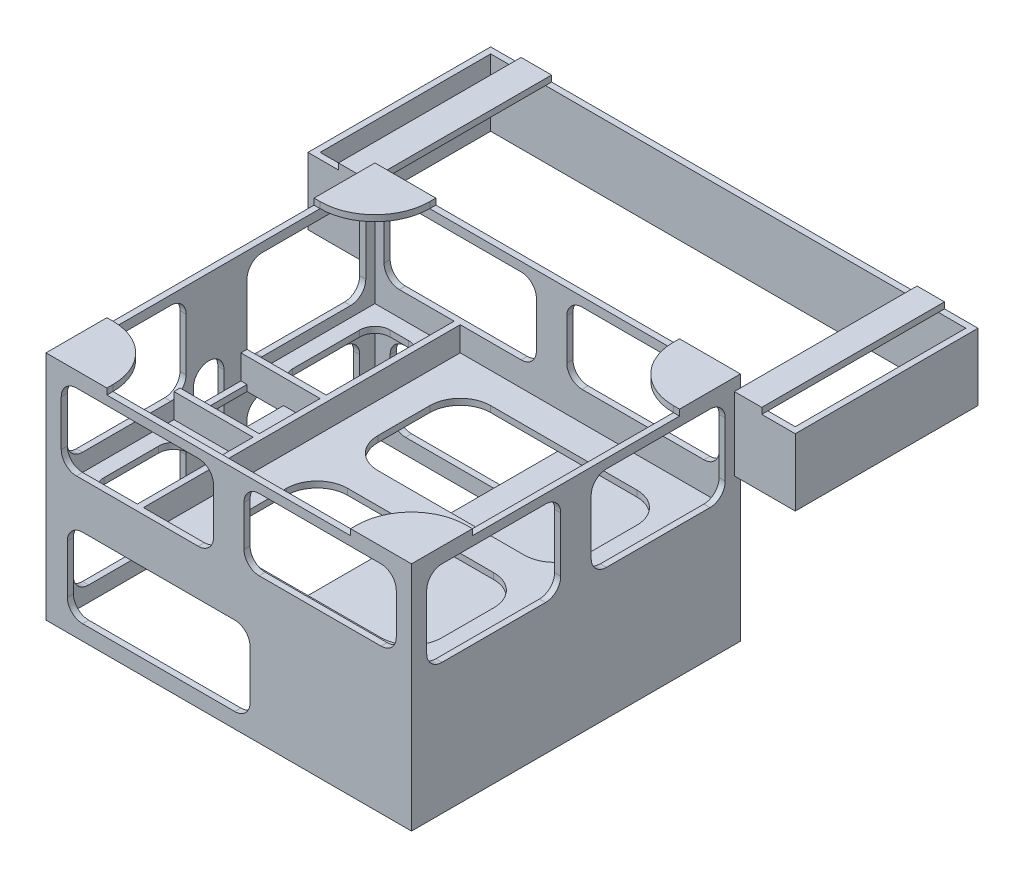
SolidWorks part; units mm, degrees
ref_plane "Front Plane" through (0, 0, 0) normal (0, 0, 1) x (1, 0, 0)
ref_plane "Top Plane" through (0, 0, 0) normal (0, 1, 0) x (1, 0, 0)
ref_plane "Right Plane" through (0, 0, 0) normal (1, 0, 0) x (0, 0, -1)
sketch "Sketch1" plane through (0, 0, 0) normal (0, 1, 0) x (1, 0, 0)
  line L1 (-113.8745, -60.9464) -> (-53.8745, -60.9464)
  line L2 (-113.8745, -60.9464) -> (-113.8745, -6.9464)
  line L3 (-113.8745, -6.9464) -> (-53.8745, -6.9464)
  line L4 (-53.8745, -60.9464) -> (-53.8745, -6.9464)
  dimension "D1" = 60
  dimension "D2" = 54
extrude "Boss-Extrude1" add sketch "Sketch1" along normal blind 38
sketch "Sketch2" plane through (0, 38, 0) normal (0, 1, 0) x (1, 0, 0)
  line L0 (-53.8745, -60.9464) -> (-53.8745, -6.9464) construction
  line L1 (-54.8745, -7.9464) -> (-98.8745, -7.9464)
  line L2 (-54.8745, -7.9464) -> (-54.8745, -59.9464)
  line L3 (-54.8745, -59.9464) -> (-98.8745, -59.9464)
  line L4 (-98.8745, -7.9464) -> (-98.8745, -59.9464)
  line L5 (-53.8745, -6.9464) -> (-113.8745, -6.9464) construction
  line L6 (-113.8745, -60.9464) -> (-53.8745, -60.9464) construction
  dimension "D1" = 1
  dimension "D2" = 1
  dimension "D3" = 1
  dimension "D4" = 44
extrude "Cut-Extrude1" cut sketch "Sketch2" against normal blind 19
sketch "Sketch3" plane through (0, 0, 0) normal (0, -1, 0) x (-1, 0, 0)
  line L0 (113.8745, -60.9464) -> (53.8745, -60.9464) construction
  line L1 (112.8745, -59.9464) -> (77.8745, -59.9464)
  line L2 (112.8745, -59.9464) -> (112.8745, -7.9464)
  line L3 (112.8745, -7.9464) -> (77.8745, -7.9464)
  line L4 (77.8745, -59.9464) -> (77.8745, -7.9464)
  line L5 (113.8745, -6.9464) -> (113.8745, -60.9464) construction
  line L6 (53.8745, -6.9464) -> (113.8745, -6.9464) construction
  dimension "D1" = 1
  dimension "D2" = 35
  dimension "D3" = 1
  dimension "D4" = 1
extrude "Cut-Extrude2" cut sketch "Sketch3" against normal blind 18
sketch "Sketch4" plane through (0, 18, 0) normal (0, -1, 0) x (-1, 0, 0)
  line L0 (77.8745, -59.9464) -> (112.8745, -59.9464) construction
  line L1 (111.8745, -39.9464) -> (105.8745, -39.9464)
  line L2 (111.8745, -39.9464) -> (111.8745, -29.9464)
  line L3 (111.8745, -29.9464) -> (105.8745, -29.9464)
  line L4 (105.8745, -39.9464) -> (105.8745, -29.9464)
  line L5 (112.8745, -7.9464) -> (77.8745, -7.9464) construction
  line L6 (112.8745, -59.9464) -> (112.8745, -7.9464) construction
  dimension "D1" = 20
  dimension "D2" = 22
  dimension "D3" = 1
  dimension "D4" = 6
extrude "Cut-Extrude3" cut sketch "Sketch4" against normal blind 38
sketch "Sketch5" plane through (0, 38, 0) normal (0, 1, 0) x (1, 0, 0)
  line L0 (-53.8745, -6.9464) -> (-113.8745, -6.9464) construction
  line L1 (-98.8745, -59.9464) -> (-112.8745, -59.9464)
  line L2 (-98.8745, -59.9464) -> (-98.8745, -7.9464)
  line L3 (-98.8745, -7.9464) -> (-112.8745, -7.9464)
  line L4 (-112.8745, -59.9464) -> (-112.8745, -7.9464)
  line L5 (-113.8745, -6.9464) -> (-113.8745, -60.9464) construction
  dimension "D1" = 1
  dimension "D2" = 1
extrude "Cut-Extrude5" cut sketch "Sketch5" against normal blind 15
sketch "Sketch6" plane through (0, 23, 0) normal (0, 1, 0) x (1, 0, 0)
  line L0 (-112.8745, -59.9464) -> (-98.8745, -59.9464) construction
  line L1 (-112.8745, -7.9464) -> (-99.8745, -7.9464)
  line L2 (-112.8745, -7.9464) -> (-112.8745, -59.9464)
  line L3 (-112.8745, -59.9464) -> (-99.8745, -59.9464)
  line L4 (-99.8745, -7.9464) -> (-99.8745, -59.9464)
  line L5 (-98.8745, -59.9464) -> (-98.8745, -7.9464) construction
  dimension "D1" = 1
extrude "Cut-Extrude6" cut sketch "Sketch6" against normal blind 4
sketch "Sketch8" plane through (0, 0, 0) normal (0, -1, 0) x (-1, 0, 0)
  line L0 (53.8745, -60.9464) -> (53.8745, -6.9464) construction
  line L1 (73.3745, -11.4464) -> (58.3745, -11.4464)
  line L2 (73.3745, -11.4464) -> (73.3745, -24.4464)
  line L3 (73.3745, -24.4464) -> (58.3745, -24.4464)
  line L4 (58.3745, -11.4464) -> (58.3745, -24.4464)
  line L6 (53.8745, -6.9464) -> (113.8745, -6.9464) construction
  dimension "D1" = 15
  dimension "D2" = 13
  dimension "D3" = 4.5
  dimension "D4" = 4.5
extrude "Cut-Extrude7" cut sketch "Sketch8" against normal blind 6
sketch "Sketch10" plane through (-73.3745, 0, 0) normal (1, 0, 0) x (0, 0, -1)
  line L0 (-11.4464, 6) -> (-11.4464, 0) construction
  line L1 (-24.4464, 6) -> (-11.4464, 6)
  line L2 (-24.4464, 6) -> (-24.4464, 1)
  line L3 (-24.4464, 1) -> (-11.4464, 1)
  line L4 (-11.4464, 6) -> (-11.4464, 1)
  line L5 (-24.4464, 0) -> (-11.4464, 0) construction
  dimension "D1" = 1
extrude "Cut-Extrude8" cut sketch "Sketch10" against normal blind 6
sketch "Sketch11" plane through (0, 0, 0) normal (0, -1, 0) x (1, 0, 0)
  line L0 (-113.8745, 60.9464) -> (-53.8745, 60.9464) construction
  line L1 (-67.8745, 50.9464) -> (-63.8745, 50.9464)
  line L2 (-67.8745, 50.9464) -> (-67.8745, 45.9464)
  line L3 (-67.8745, 45.9464) -> (-63.8745, 45.9464)
  line L4 (-63.8745, 50.9464) -> (-63.8745, 45.9464)
  line L5 (-53.8745, 60.9464) -> (-53.8745, 6.9464) construction
  dimension "D1" = 4
  dimension "D2" = 5
  dimension "D3" = 10
  dimension "D4" = 10
extrude "Cut-Extrude9" cut sketch "Sketch11" against normal blind 3
sketch "Sketch12" plane through (-67.8745, 0, 0) normal (1, 0, 0) x (0, 0, -1)
  line L0 (-50.9464, 3) -> (-50.9464, 0) construction
  line L1 (-45.9464, 3) -> (-50.9464, 3)
  line L2 (-45.9464, 3) -> (-45.9464, 1)
  line L3 (-45.9464, 1) -> (-50.9464, 1)
  line L4 (-50.9464, 3) -> (-50.9464, 1)
  line L5 (-50.9464, 0) -> (-45.9464, 0) construction
  dimension "D1" = 1
extrude "Cut-Extrude10" cut sketch "Sketch12" against normal blind 13
sketch "Sketch13" plane through (-113.8745, 0, 0) normal (-1, 0, 0) x (0, 0, 1)
  line L0 (35.233, 15) -> (35.233, 22) construction
  line L1 (32.733, 15) -> (32.733, 22)
  line L2 (37.733, 15) -> (37.733, 22)
  line L3 (59.9464, 18) -> (7.9464, 18) construction
  line L4 (39.9464, 19) -> (29.9464, 19) construction
  arc A0 (32.733, 15) -> (37.733, 15) centre (35.233, 15) ccw
  arc A1 (37.733, 22) -> (32.733, 22) centre (35.233, 22) ccw
  point P2 (35.233, 18.5)
  dimension "D1" = 3
  dimension "D2" = 3
  dimension "D3" = 2.5
extrude "Cut-Extrude11" cut sketch "Sketch13" against normal blind 1
sketch "Sketch14" plane through (0, 19, 0) normal (0, 1, 0) x (1, 0, 0)
  line L0 (-99.8745, -59.9464) -> (-99.8745, -7.9464) construction
  line L1 (-112.8745, -40.9464) -> (-99.8745, -40.9464)
  line L2 (-112.8745, -40.9464) -> (-112.8745, -39.9464)
  line L3 (-112.8745, -39.9464) -> (-99.8745, -39.9464)
  line L4 (-99.8745, -40.9464) -> (-99.8745, -39.9464)
  line L5 (-112.8745, -37.733) -> (-112.8745, -59.9464) construction
  line L6 (-105.8745, -39.9464) -> (-111.8745, -39.9464) construction
  dimension "D1" = 0
  dimension "D2" = 1
  dimension "D3" = 0
extrude "Boss-Extrude2" add sketch "Sketch14" along normal blind 4
sketch "Sketch15" plane through (0, 19, 0) normal (0, 1, 0) x (1, 0, 0)
  line L0 (-112.8745, -7.9464) -> (-112.8745, -32.733) construction
  line L1 (-112.8745, -29.9464) -> (-99.8745, -29.9464)
  line L2 (-112.8745, -29.9464) -> (-112.8745, -28.9464)
  line L3 (-112.8745, -28.9464) -> (-99.8745, -28.9464)
  line L4 (-99.8745, -29.9464) -> (-99.8745, -28.9464)
  line L5 (-99.8745, -39.9464) -> (-99.8745, -7.9464) construction
  line L6 (-111.8745, -29.9464) -> (-105.8745, -29.9464) construction
  dimension "D1" = 0
  dimension "D2" = 1
extrude "Boss-Extrude3" add sketch "Sketch15" along normal blind 4
sketch "Sketch16" plane through (0, 19, 0) normal (0, 1, 0) x (1, 0, 0)
  line L0 (-98.8745, -59.9464) -> (-54.8745, -59.9464) construction
  line L1 (-64.8745, -54.9464) -> (-88.8745, -54.9464)
  line L2 (-59.8745, -49.9464) -> (-59.8745, -41.4464)
  line L3 (-64.8745, -36.4464) -> (-88.8745, -36.4464)
  line L4 (-93.8745, -49.9464) -> (-93.8745, -41.4464)
  line L5 (-88.8745, -31.4464) -> (-64.8745, -31.4464)
  line L6 (-93.8745, -26.4464) -> (-93.8745, -17.9464)
  line L7 (-88.8745, -12.9464) -> (-64.8745, -12.9464)
  line L8 (-59.8745, -26.4464) -> (-59.8745, -17.9464)
  line L9 (-54.8745, -59.9464) -> (-54.8745, -7.9464) construction
  line L10 (-98.8745, -7.9464) -> (-98.8745, -59.9464) construction
  line L11 (-54.8745, -7.9464) -> (-98.8745, -7.9464) construction
  arc A0 (-64.8745, -31.4464) -> (-59.8745, -26.4464) centre (-64.8745, -26.4464) ccw
  arc A1 (-64.8745, -12.9464) -> (-59.8745, -17.9464) centre (-64.8745, -17.9464) cw
  arc A2 (-93.8745, -17.9464) -> (-88.8745, -12.9464) centre (-88.8745, -17.9464) cw
  arc A3 (-88.8745, -31.4464) -> (-93.8745, -26.4464) centre (-88.8745, -26.4464) cw
  arc A4 (-88.8745, -54.9464) -> (-93.8745, -49.9464) centre (-88.8745, -49.9464) cw
  arc A5 (-88.8745, -36.4464) -> (-93.8745, -41.4464) centre (-88.8745, -41.4464) ccw
  arc A6 (-59.8745, -41.4464) -> (-64.8745, -36.4464) centre (-64.8745, -41.4464) ccw
  arc A7 (-64.8745, -54.9464) -> (-59.8745, -49.9464) centre (-64.8745, -49.9464) ccw
  point P22 (-93.8745, -12.9464)
  point P25 (-93.8745, -31.4464)
  dimension "D9" = 5
  dimension "D1" = 5
  dimension "D2" = 5
  dimension "D3" = 5
  dimension "D4" = 5
  dimension "D5" = 5
  dimension "D6" = 5
  dimension "D7" = 5
  dimension "D8" = 18.5
extrude "Cut-Extrude12" cut sketch "Sketch16" against normal blind 1
sketch "Sketch17" plane through (0, 19, 0) normal (0, 1, 0) x (1, 0, 0)
  line L0 (-112.8745, -40.9464) -> (-112.8745, -59.9464) construction
  line L1 (-104.8745, -57.4464) -> (-107.8745, -57.4464)
  line L2 (-102.3745, -54.9464) -> (-102.3745, -45.9464)
  line L3 (-104.8745, -43.4464) -> (-107.8745, -43.4464)
  line L4 (-110.3745, -54.9464) -> (-110.3745, -45.9464)
  line L5 (-104.8745, -26.4464) -> (-107.8745, -26.4464)
  line L6 (-102.3745, -23.9464) -> (-102.3745, -12.9464)
  line L7 (-104.8745, -10.4464) -> (-107.8745, -10.4464)
  line L8 (-110.3745, -23.9464) -> (-110.3745, -12.9464)
  line L9 (-99.8745, -59.9464) -> (-99.8745, -40.9464) construction
  line L10 (-112.8745, -40.9464) -> (-99.8745, -40.9464) construction
  line L11 (-112.8745, -59.9464) -> (-99.8745, -59.9464) construction
  line L12 (-99.8745, -28.9464) -> (-112.8745, -28.9464) construction
  line L13 (-112.8745, -7.9464) -> (-112.8745, -28.9464) construction
  line L14 (-99.8745, -28.9464) -> (-99.8745, -7.9464) construction
  line L15 (-99.8745, -7.9464) -> (-112.8745, -7.9464) construction
  arc A0 (-102.3745, -12.9464) -> (-104.8745, -10.4464) centre (-104.8745, -12.9464) ccw
  arc A1 (-107.8745, -10.4464) -> (-110.3745, -12.9464) centre (-107.8745, -12.9464) ccw
  arc A2 (-107.8745, -26.4464) -> (-110.3745, -23.9464) centre (-107.8745, -23.9464) cw
  arc A3 (-104.8745, -26.4464) -> (-102.3745, -23.9464) centre (-104.8745, -23.9464) ccw
  arc A4 (-102.3745, -45.9464) -> (-104.8745, -43.4464) centre (-104.8745, -45.9464) ccw
  arc A5 (-107.8745, -43.4464) -> (-110.3745, -45.9464) centre (-107.8745, -45.9464) ccw
  arc A6 (-107.8745, -57.4464) -> (-110.3745, -54.9464) centre (-107.8745, -54.9464) cw
  arc A7 (-104.8745, -57.4464) -> (-102.3745, -54.9464) centre (-104.8745, -54.9464) ccw
  dimension "D9" = 2.5
  dimension "D1" = 2.5
  dimension "D2" = 2.5
  dimension "D3" = 2.5
  dimension "D4" = 2.5
  dimension "D5" = 2.5
  dimension "D6" = 2.5
  dimension "D7" = 2.5
  dimension "D8" = 2.5
extrude "Cut-Extrude13" cut sketch "Sketch17" against normal blind 1
sketch "Sketch18" plane through (-53.8745, 0, 0) normal (1, 0, 0) x (0, 0, -1)
  line L0 (-60.9464, 38) -> (-6.9464, 38) construction
  line L1 (-55.9464, 35.5) -> (-38.9464, 35.5)
  line L2 (-58.4464, 33) -> (-58.4464, 24)
  line L3 (-55.9464, 21.5) -> (-38.9464, 21.5)
  line L4 (-36.4464, 33) -> (-36.4464, 24)
  line L5 (-28.9464, 35.5) -> (-11.9464, 35.5)
  line L6 (-31.4464, 33) -> (-31.4464, 24)
  line L7 (-28.9464, 21.5) -> (-11.9464, 21.5)
  line L8 (-9.4464, 33) -> (-9.4464, 24)
  line L9 (-60.9464, 38) -> (-60.9464, 0) construction
  line L10 (-6.9464, 38) -> (-6.9464, 0) construction
  line L11 (-59.9464, 19) -> (-7.9464, 19) construction
  arc A0 (-31.4464, 24) -> (-28.9464, 21.5) centre (-28.9464, 24) ccw
  arc A1 (-11.9464, 21.5) -> (-9.4464, 24) centre (-11.9464, 24) ccw
  arc A2 (-11.9464, 35.5) -> (-9.4464, 33) centre (-11.9464, 33) cw
  arc A3 (-28.9464, 35.5) -> (-31.4464, 33) centre (-28.9464, 33) ccw
  arc A4 (-58.4464, 24) -> (-55.9464, 21.5) centre (-55.9464, 24) ccw
  arc A5 (-38.9464, 21.5) -> (-36.4464, 24) centre (-38.9464, 24) ccw
  arc A6 (-38.9464, 35.5) -> (-36.4464, 33) centre (-38.9464, 33) cw
  arc A7 (-55.9464, 35.5) -> (-58.4464, 33) centre (-55.9464, 33) ccw
  point P26 (-58.4464, 21.5)
  point P29 (-36.4464, 21.5)
  dimension "D9" = 2.5
  dimension "D1" = 2.5
  dimension "D2" = 2.5
  dimension "D3" = 2.5
  dimension "D4" = 2.5
  dimension "D5" = 5
  dimension "D6" = 22
  dimension "D7" = 2.5
  dimension "D8" = 2.5
extrude "Cut-Extrude14" cut sketch "Sketch18" against normal blind 1
sketch "Sketch19" plane through (0, 0, 6.9464) normal (0, 0, -1) x (-1, 0, 0)
  line L0 (53.8745, 38) -> (113.8745, 38) construction
  line L1 (58.8745, 35.5) -> (78.8745, 35.5)
  line L2 (56.3745, 33) -> (56.3745, 26.3041)
  line L3 (58.8745, 23.8041) -> (78.8745, 23.8041)
  line L4 (81.3745, 33) -> (81.3745, 26.3041)
  line L5 (88.8745, 35.5) -> (108.8745, 35.5)
  line L6 (86.3745, 33) -> (86.3745, 25.5)
  line L7 (88.8745, 23) -> (108.8745, 23)
  line L8 (111.3745, 33) -> (111.3745, 25.5)
  line L9 (113.8745, 38) -> (113.8745, 0) construction
  line L10 (53.8745, 38) -> (53.8745, 0) construction
  arc A0 (108.8745, 23) -> (111.3745, 25.5) centre (108.8745, 25.5) ccw
  arc A1 (108.8745, 35.5) -> (111.3745, 33) centre (108.8745, 33) cw
  arc A2 (88.8745, 35.5) -> (86.3745, 33) centre (88.8745, 33) ccw
  arc A3 (86.3745, 25.5) -> (88.8745, 23) centre (88.8745, 25.5) ccw
  arc A4 (78.8745, 23.8041) -> (81.3745, 26.3041) centre (78.8745, 26.3041) ccw
  arc A5 (78.8745, 35.5) -> (81.3745, 33) centre (78.8745, 33) cw
  arc A6 (56.3745, 26.3041) -> (58.8745, 23.8041) centre (58.8745, 26.3041) ccw
  arc A7 (58.8745, 35.5) -> (56.3745, 33) centre (58.8745, 33) ccw
  point P17 (111.3745, 23)
  point P24 (86.3745, 23)
  dimension "D8" = 2.5
  dimension "D1" = 2.5
  dimension "D2" = 2.5
  dimension "D3" = 2.5
  dimension "D4" = 2.5
  dimension "D5" = 5
  dimension "D6" = 25
  dimension "D7" = 0
extrude "Cut-Extrude15" cut sketch "Sketch19" against normal blind 60
sketch "Sketch20" plane through (-113.8745, 0, 0) normal (-1, 0, 0) x (0, 0, 1)
  line L0 (59.9464, 38) -> (7.9464, 38) construction
  line L1 (11.9464, 35.5) -> (26.4464, 35.5)
  line L2 (9.4464, 33) -> (9.4464, 23.222)
  line L3 (11.9464, 20.722) -> (26.4464, 20.722)
  line L4 (28.9464, 33) -> (28.9464, 23.222)
  line L5 (41.4464, 35.5) -> (55.9464, 35.5)
  line L6 (38.9464, 33) -> (38.9464, 24.3756)
  line L7 (41.4464, 21.8756) -> (55.9464, 21.8756)
  line L8 (58.4464, 33) -> (58.4464, 24.3756)
  line L9 (6.9464, 38) -> (6.9464, 0) construction
  line L10 (60.9464, 38) -> (60.9464, 0) construction
  line L11 (6.9464, 38) -> (60.9464, 38) construction
  arc A0 (38.9464, 24.3756) -> (41.4464, 21.8756) centre (41.4464, 24.3756) ccw
  arc A1 (55.9464, 21.8756) -> (58.4464, 24.3756) centre (55.9464, 24.3756) ccw
  arc A2 (55.9464, 35.5) -> (58.4464, 33) centre (55.9464, 33) cw
  arc A3 (41.4464, 35.5) -> (38.9464, 33) centre (41.4464, 33) ccw
  arc A4 (9.4464, 23.222) -> (11.9464, 20.722) centre (11.9464, 23.222) ccw
  arc A5 (26.4464, 20.722) -> (28.9464, 23.222) centre (26.4464, 23.222) ccw
  arc A6 (26.4464, 35.5) -> (28.9464, 33) centre (26.4464, 33) cw
  arc A7 (11.9464, 35.5) -> (9.4464, 33) centre (11.9464, 33) ccw
  point P18 (38.9464, 21.8756)
  point P21 (58.4464, 21.8756)
  dimension "D7" = 2.5
  dimension "D1" = 2.5
  dimension "D2" = 2.5
  dimension "D3" = 10
  dimension "D4" = 2.5
  dimension "D5" = 2.5
  dimension "D6" = 19.5
extrude "Cut-Extrude16" cut sketch "Sketch20" against normal blind 1
sketch "Sketch21" plane through (0, 0, 59.9464) normal (0, 0, -1) x (-1, 0, 0)
  line L0 (77.8745, 0) -> (112.8745, 0) construction
  line L1 (107.8745, 2.5) -> (82.8745, 2.5)
  line L2 (110.3745, 5) -> (110.3745, 13)
  line L3 (107.8745, 15.5) -> (82.8745, 15.5)
  line L4 (80.3745, 5) -> (80.3745, 13)
  line L5 (77.8745, 18) -> (77.8745, 0) construction
  line L6 (112.8745, 18) -> (112.8745, 0) construction
  line L7 (77.8745, 18) -> (112.8745, 18) construction
  arc A0 (110.3745, 13) -> (107.8745, 15.5) centre (107.8745, 13) ccw
  arc A1 (82.8745, 15.5) -> (80.3745, 13) centre (82.8745, 13) ccw
  arc A2 (82.8745, 2.5) -> (80.3745, 5) centre (82.8745, 5) cw
  arc A3 (107.8745, 2.5) -> (110.3745, 5) centre (107.8745, 5) ccw
  dimension "D5" = 2.5
  dimension "D1" = 2.5
  dimension "D2" = 2.5
  dimension "D3" = 2.5
  dimension "D4" = 2.5
extrude "Cut-Extrude17" cut sketch "Sketch21" along normal blind 100 and the other way blind 10
sketch "Sketch22" plane through (-112.8745, 0, 0) normal (1, 0, 0) x (0, 0, -1)
  line L0 (-59.9464, 0) -> (-7.9464, 0) construction
  line L1 (-12.9464, 2.5) -> (-26.4464, 2.5)
  line L2 (-10.4464, 5) -> (-10.4464, 13)
  line L3 (-12.9464, 15.5) -> (-26.4464, 15.5)
  line L4 (-28.9464, 5) -> (-28.9464, 13)
  line L5 (-41.4464, 2.5) -> (-54.9464, 2.5)
  line L6 (-38.9464, 5) -> (-38.9464, 13)
  line L7 (-41.4464, 15.5) -> (-54.9464, 15.5)
  line L8 (-57.4464, 5) -> (-57.4464, 13)
  line L9 (-7.9464, 18) -> (-7.9464, 0) construction
  line L10 (-32.733, 18) -> (-7.9464, 18) construction
  line L11 (-59.9464, 18) -> (-37.733, 18) construction
  line L12 (-59.9464, 18) -> (-59.9464, 0) construction
  arc A0 (-38.9464, 13) -> (-41.4464, 15.5) centre (-41.4464, 13) ccw
  arc A1 (-54.9464, 15.5) -> (-57.4464, 13) centre (-54.9464, 13) ccw
  arc A2 (-54.9464, 2.5) -> (-57.4464, 5) centre (-54.9464, 5) cw
  arc A3 (-41.4464, 2.5) -> (-38.9464, 5) centre (-41.4464, 5) ccw
  arc A4 (-26.4464, 2.5) -> (-28.9464, 5) centre (-26.4464, 5) cw
  arc A5 (-26.4464, 15.5) -> (-28.9464, 13) centre (-26.4464, 13) ccw
  arc A6 (-10.4464, 13) -> (-12.9464, 15.5) centre (-12.9464, 13) ccw
  arc A7 (-12.9464, 2.5) -> (-10.4464, 5) centre (-12.9464, 5) ccw
  point P30 (-28.9464, 15.5)
  point P33 (-10.4464, 15.5)
  dimension "D9" = 2.5
  dimension "D1" = 2.5
  dimension "D2" = 10
  dimension "D3" = 2.5
  dimension "D4" = 2.5
  dimension "D5" = 2.5
  dimension "D6" = 2.5
  dimension "D7" = 2.5
  dimension "D8" = 18.5
extrude "Cut-Extrude18" cut sketch "Sketch22" against normal blind 10
sketch "Sketch23" plane through (0, 38, 0) normal (0, 1, 0) x (1, 0, 0)
  line L1 (-112.8745, -59.9464) -> (-54.8745, -59.9464)
  line L2 (-112.8745, -59.9464) -> (-112.8745, -7.9464)
  line L3 (-112.8745, -7.9464) -> (-54.8745, -7.9464)
  line L4 (-54.8745, -59.9464) -> (-54.8745, -7.9464)
extrude "Boss-Extrude4" add sketch "Sketch23" against normal blind 1
sketch "Sketch24" plane through (0, 38, 0) normal (0, 1, 0) x (1, 0, 0)
  line L0 (-113.8745, -6.9464) -> (-113.8745, -60.9464) construction
  line L1 (-113.8745, -50.9464) -> (-53.8745, -50.9464)
  line L2 (-113.8745, -50.9464) -> (-113.8745, -16.9464)
  line L3 (-113.8745, -16.9464) -> (-53.8745, -16.9464)
  line L4 (-53.8745, -50.9464) -> (-53.8745, -16.9464)
  line L5 (-53.8745, -60.9464) -> (-53.8745, -6.9464) construction
  line L6 (-53.8745, -6.9464) -> (-113.8745, -6.9464) construction
  line L7 (-103.8745, -6.9464) -> (-63.8745, -6.9464)
  line L8 (-103.8745, -6.9464) -> (-103.8745, -60.9464)
  line L9 (-103.8745, -60.9464) -> (-63.8745, -60.9464)
  line L10 (-63.8745, -6.9464) -> (-63.8745, -60.9464)
  line L11 (-113.8745, -60.9464) -> (-53.8745, -60.9464) construction
  line L12 (-58.8745, -60.9464) -> (-56.3745, -60.9464) construction
  line M5 (-113.8745, -6.9464) -> (-113.8745, -60.9464)
  line M6 (-113.8745, -60.9464) -> (-53.8745, -60.9464)
  line M7 (-53.8745, -60.9464) -> (-53.8745, -6.9464)
  line M8 (-53.8745, -6.9464) -> (-113.8745, -6.9464)
  dimension "D1" = 10
  dimension "D2" = 10
  dimension "D3" = 10
  dimension "D4" = 10
extrude "Cut-Extrude20" cut sketch "Sketch24" against normal blind 1 contours L10 L1 L8 M6 | L3 L10 L1 M7 | L10 L8 L3 M8 | L10 L3 L8 L1 | L8 L3 L1 M5
fillet "Fillet1" radius 9 3 edges at (-103.8745, 37, 55.4464) (-108.3745, 37, 50.9464) (-103.8745, 37.5, 50.9464)
fillet "Fillet2" radius 9 3 edges at (-63.8745, 37, 12.4464) (-59.3745, 37, 16.9464) (-63.8745, 37.5, 16.9464)
fillet "Fillet3" radius 9 3 edges at (-63.8745, 37, 55.4464) (-63.8745, 37.5, 50.9464) (-59.3745, 37, 50.9464)
fillet "Fillet4" radius 9 3 edges at (-108.3745, 37, 16.9464) (-103.8745, 37, 12.4464) (-103.8745, 37.5, 16.9464)
sketch "Sketch27" plane through (0, 0, 6.9464) normal (0, 0, -1) x (-1, 0, 0)
  line L0 (53.8745, 38) -> (53.8745, 0) construction
  line L1 (53.8745, 24) -> (43.8745, 24)
  line L2 (53.8745, 24) -> (53.8745, 35)
  line L3 (53.8745, 35) -> (43.8745, 35)
  line L4 (43.8745, 24) -> (43.8745, 35)
  line L5 (113.8745, 38) -> (113.8745, 0) construction
  line L6 (113.8745, 24) -> (123.8745, 24)
  line L7 (113.8745, 24) -> (113.8745, 35)
  line L8 (113.8745, 35) -> (123.8745, 35)
  line L9 (123.8745, 24) -> (123.8745, 35)
  line L10 (63.8745, 37) -> (103.8745, 37) construction
  dimension "D1" = 2
  dimension "D2" = 2
  dimension "D3" = 80
  dimension "D4" = 10
  dimension "D5" = 11
  dimension "D6" = 11
extrude "Boss-Extrude10" add sketch "Sketch27" against normal blind 1
sketch "Sketch31" plane through (0, 0, 6.9464) normal (0, 0, -1) x (-1, 0, 0)
  line L0 (43.8745, 24) -> (53.8745, 24) construction
  line L1 (43.8745, 24) -> (44.8745, 24)
  line L2 (43.8745, 24) -> (43.8745, 35)
  line L3 (43.8745, 35) -> (44.8745, 35)
  line L4 (44.8745, 24) -> (44.8745, 35)
  line L5 (53.8745, 35) -> (43.8745, 35) construction
  line L6 (123.8745, 35) -> (113.8745, 35) construction
  line L7 (122.8745, 35) -> (123.8745, 35)
  line L8 (122.8745, 35) -> (122.8745, 24)
  line L9 (122.8745, 24) -> (123.8745, 24)
  line L10 (123.8745, 35) -> (123.8745, 24)
  point P14 (94.427, 25.5002)
  dimension "D1" = 1
  dimension "D2" = 1
extrude "Boss-Extrude12" add sketch "Sketch31" along normal blind 29
sketch "Sketch33" plane through (-44.8745, 0, 0) normal (-1, 0, 0) x (0, 0, 1)
  line L0 (-22.0536, 24) -> (6.9464, 24) construction
  line L1 (-22.0536, 35) -> (-21.0536, 35)
  line L2 (-22.0536, 35) -> (-22.0536, 24)
  line L3 (-22.0536, 24) -> (-21.0536, 24)
  line L4 (-21.0536, 35) -> (-21.0536, 24)
  dimension "D1" = 1
extrude "Boss-Extrude13" add sketch "Sketch33" along normal blind 78
sketch "Sketch34" plane through (0, 35, 0) normal (0, 1, 0) x (1, 0, 0)
  line L0 (-123.8745, -7.9464) -> (-113.8745, -7.9464) construction
  line L1 (-123.8745, 22.0536) -> (-43.8745, 22.0536) construction
  line L2 (-118.8745, -7.9464) -> (-113.8745, -7.9464)
  line L3 (-118.8745, -7.9464) -> (-118.8745, 22.0536)
  line L4 (-118.8745, 22.0536) -> (-113.8745, 22.0536)
  line L5 (-113.8745, -7.9464) -> (-113.8745, 22.0536)
  line L7 (-53.8745, -7.9464) -> (-49.3745, -7.9464)
  line L8 (-53.8745, -7.9464) -> (-53.8745, 22.0536)
  line L9 (-53.8745, 22.0536) -> (-49.3745, 22.0536)
  line L10 (-49.3745, -7.9464) -> (-49.3745, 22.0536)
extrude "Boss-Extrude14" add sketch "Sketch34" along normal blind 1
